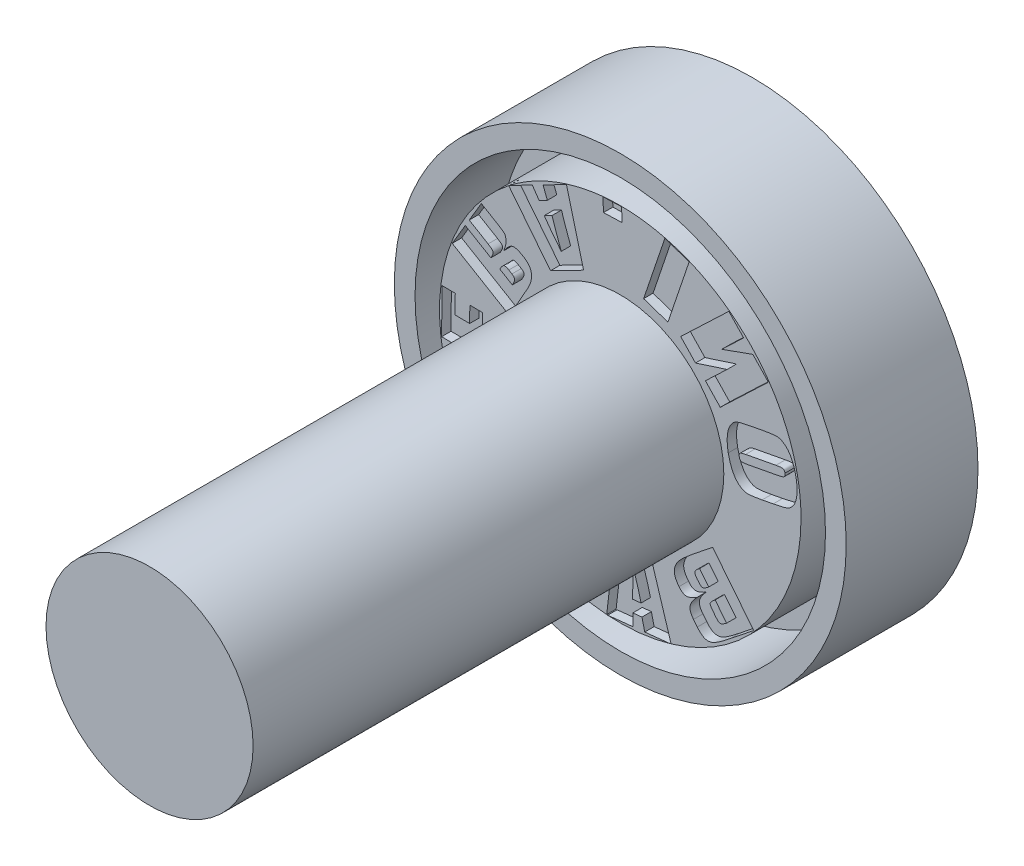
SolidWorks part; units mm, degrees
ref_plane "Alzado" through (0, 0, 0) normal (0, 0, 1) x (1, 0, 0)
ref_plane "Planta" through (0, 0, 0) normal (0, 1, 0) x (1, 0, 0)
ref_plane "Vista lateral" through (0, 0, 0) normal (1, 0, 0) x (0, 0, -1)
sketch "Croquis1" plane through (0, 0, 0) normal (0, 0, 1) x (1, 0, 0)
  circle A0 centre (0, 0) radius 12
  dimension "D1" = 24
extrude "Saliente-Extruir1" add sketch "Croquis1" along normal blind 7
sketch "Croquis2" plane through (0, 0, 7) normal (0, 0, 1) x (1, 0, 0)
  circle A0 centre (0, 0) radius 9.6
  circle A1 centre (0, 0) radius 10.9
  dimension "D1" = 19.2
  dimension "D2" = 21.8
extrude "Cortar-Extruir1" cut sketch "Croquis2" against normal blind 4.5
sketch "Croquis3" plane through (0, 0, 7) normal (0, 0, 1) x (1, 0, 0)
  circle A0 centre (0, 0) radius 5.5
  dimension "D1" = 11
extrude "Saliente-Extruir2" add sketch "Croquis3" along normal blind 25
sketch "Croquis5" plane through (0, 0, 7) normal (0, 0, 1) x (1, 0, 0)
  text T0 "BARRERA.INO" font "Impact" height 3.5
extrude "Cortar-Extruir2" cut sketch "Croquis5" against normal blind 0.5
